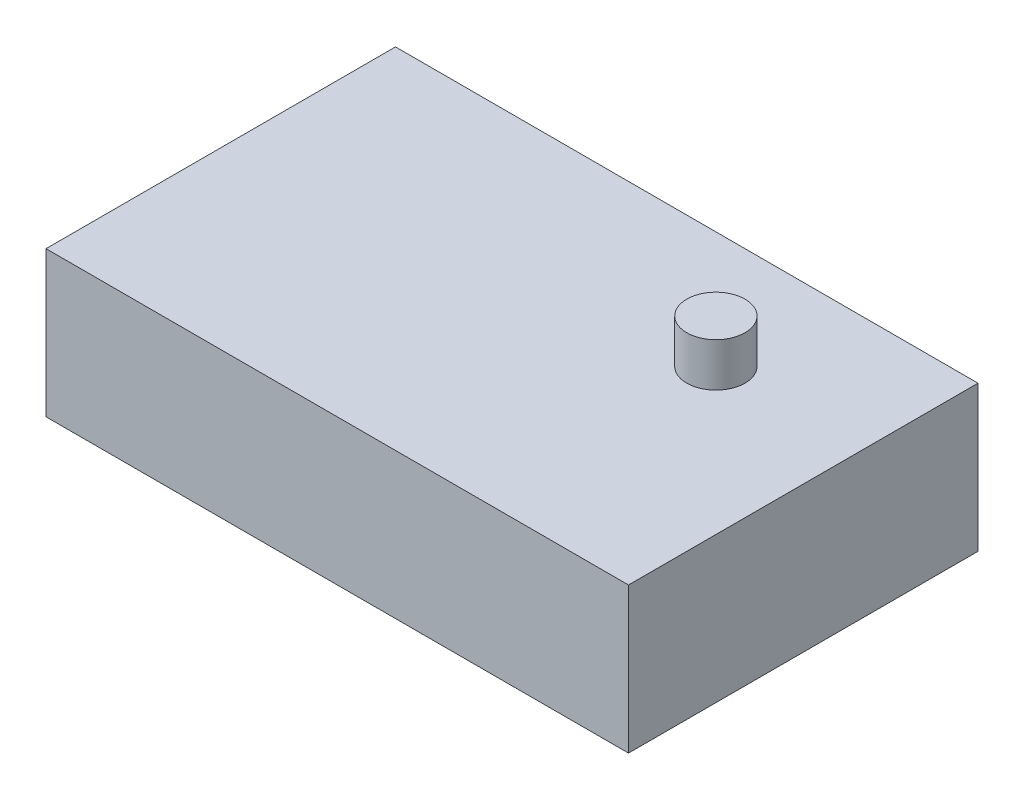
SolidWorks part; units mm, degrees
ref_plane "Front Plane" through (0, 0, 0) normal (0, 0, 1) x (1, 0, 0)
ref_plane "Top Plane" through (0, 0, 0) normal (0, 1, 0) x (1, 0, 0)
ref_plane "Right Plane" through (0, 0, 0) normal (1, 0, 0) x (0, 0, -1)
sketch "Sketch1" plane through (0, 0, 0) normal (0, 1, 0) x (1, 0, 0)
  line L1 (10, -6) -> (-10, -6)
  line L2 (10, -6) -> (10, 6)
  line L3 (10, 6) -> (-10, 6)
  line L4 (-10, -6) -> (-10, 6)
  line L5 (10, -6) -> (-10, 6) construction
  line L6 (10, 6) -> (-10, -6) construction
  point P0 (0, 0)
  dimension "D1" = 20
  dimension "D2" = 12
extrude "Boss-Extrude1" add sketch "Sketch1" along normal blind 5
ref_plane "Plane1" through (0, 5, 0) normal (0, 1, 0) x (1, 0, 0)
sketch "Sketch2" plane through (0, 5, 0) normal (0, 1, 0) x (1, 0, 0)
  line L0 (10, 6) -> (-10, 6) construction
  circle A0 centre (5, 2) radius 1
  dimension "D2" = 2
  dimension "D1" = 4
extrude "Boss-Extrude2" add sketch "Sketch2" along normal blind 1.5
